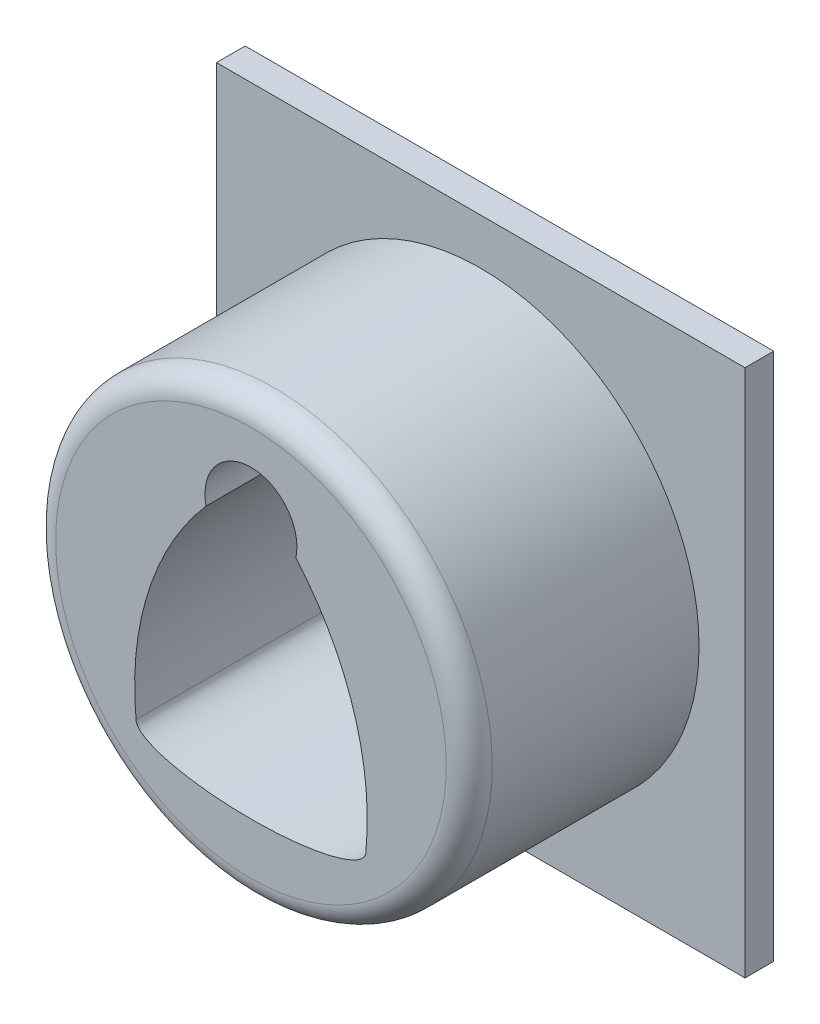
SolidWorks part; units mm, degrees
ref_plane "Спереди" through (0, 0, 0) normal (0, 0, 1) x (1, 0, 0)
ref_plane "Сверху" through (0, 0, 0) normal (0, 1, 0) x (1, 0, 0)
ref_plane "Справа" through (0, 0, 0) normal (1, 0, 0) x (0, 0, -1)
sketch "Эскиз1" plane through (0, 0, 0) normal (0, 0, 1) x (1, 0, 0)
  circle A0 centre (0, 0) radius 3.8
  dimension "D1" = 7.6
extrude "Бобышка-Вытянуть1" add sketch "Эскиз1" along normal blind 4
sketch "Эскиз2" plane through (0, 0, 0) normal (0, 0, -1) x (-1, 0, 0)
  line L1 (-4.6, 4.6) -> (4.6, 4.6)
  line L2 (-4.6, 4.6) -> (-4.6, -4.6)
  line L3 (-4.6, -4.6) -> (4.6, -4.6)
  line L4 (4.6, 4.6) -> (4.6, -4.6)
  circle A0 centre (0, 0) radius 3.8 construction
  dimension "D1" = 4.6
  dimension "D2" = 4.6
  dimension "D3" = 4.6
  dimension "D4" = 4.6
extrude "Бобышка-Вытянуть2" add sketch "Эскиз2" along normal blind 0.5
fillet "Скругление1" radius 0.4 1 edges at (3.8, 0, 4)
sketch "Эскиз7" plane through (0, 0, 4) normal (0, 0, 1) x (1, 0, 0)
  line L0 (0, 0) -> (0, -8.3052) construction
  line L1 (-8.8208, -2.0038) -> (9.4991, -2.0038) construction
  circle A1 centre (0, 2) radius 0.8
  circle A2 centre (0, 0) radius 3.8 construction
  circle A3 centre (0, 0) radius 3.4 construction
  arc A4 (-2, -2.0038) -> (-0.7805, 1.8246) centre (3.0494, -1.5038) cw
  arc A5 (2, -2.0038) -> (0.7805, 1.8246) centre (-3.0494, -1.5038) ccw
  ellipse E0 centre (0, -2.0038) end of major axis (2, -2.0038) minor radius 0.5
  dimension "D4" = 1.6
  dimension "D5" = 2
  dimension "D1" = 2.0038
  dimension "D2" = 2
  dimension "D3" = 0.5
extrude "Вырез-Вытянуть4" cut sketch "Эскиз7" against normal blind 4 contours E0 A5 A1 A4 | E0 | A1
sketch "Эскиз8" plane through (0, 0, 0) normal (0, 0, 1) x (1, 0, 0)
  circle A0 centre (0, 0) radius 0.6
  dimension "D1" = 1.2
extrude "Вырез-Вытянуть5" cut sketch "Эскиз8" against normal through all
